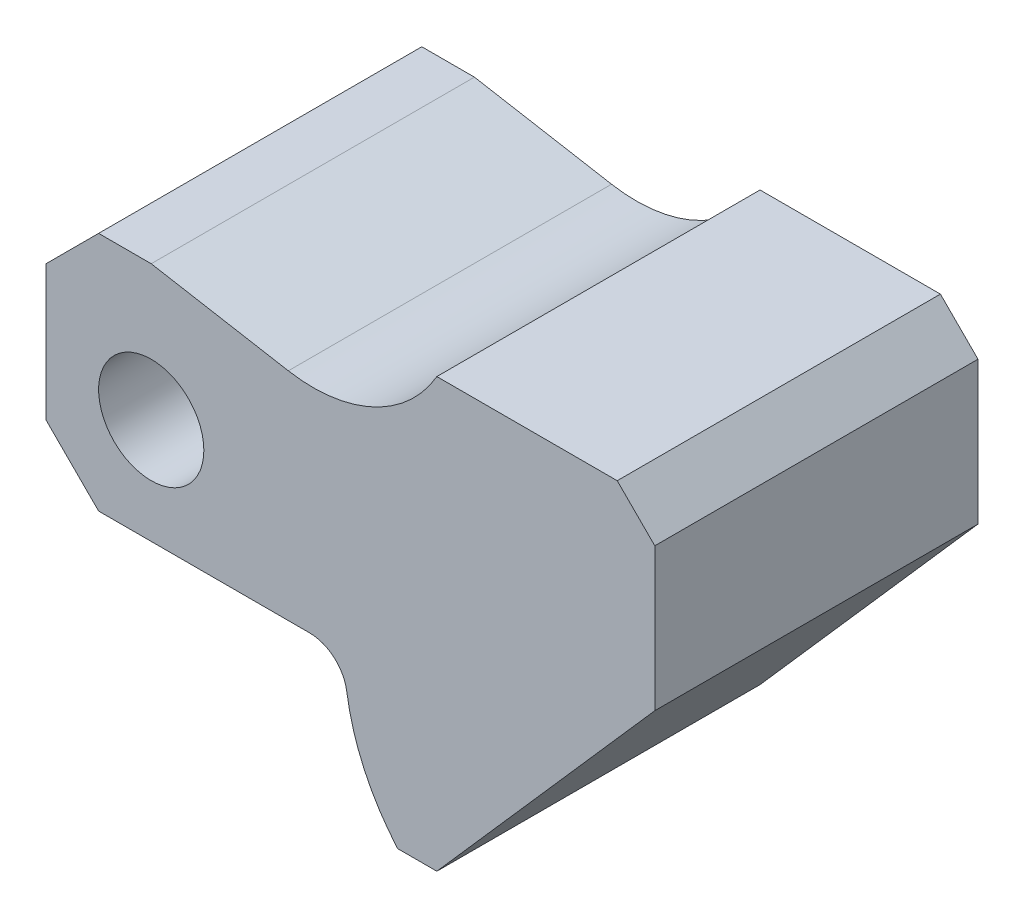
SolidWorks part; units mm, degrees
ref_plane "前基準面" through (0, 0, 0) normal (0, 0, 1) x (1, 0, 0)
ref_plane "上基準面" through (0, 0, 0) normal (0, 1, 0) x (1, 0, 0)
ref_plane "右基準面" through (0, 0, 0) normal (1, 0, 0) x (0, 0, -1)
sketch "草圖2" plane through (0, 0, 0) normal (0, 0, 1) x (1, 0, 0)
  line L0 (0, 0) -> (22.7674, 0) construction
  line L1 (0, 0) -> (0, 19.8285) construction
  line L2 (-14, 11) -> (-14, -7)
  line L3 (-14, -7) -> (-7, -14)
  line L4 (-7, -14) -> (21.0666, -14)
  line L5 (-14, 11) -> (-7, 18)
  line L6 (-7, 18) -> (0, 18)
  line L7 (0, 18) -> (18.2431, 14.7833)
  line L8 (38, 24) -> (62, 24)
  line L9 (62, 24) -> (67, 19)
  line L10 (67, 19) -> (67, 0)
  line L11 (67, 0) -> (38, -33)
  line L12 (38, -33) -> (32.7881, -33)
  circle A0 centre (0, 0) radius 7
  arc A1 (18.2431, 14.7833) -> (38, 24) centre (21.5424, 33.4946) ccw
  arc A2 (21.0666, -14) -> (26.0123, -18.2647) centre (21.0666, -19) cw
  arc A3 (26.0123, -18.2647) -> (32.7881, -33) centre (54.697, -14) ccw
  point P2 (-3.5, 18)
  point P15 (0, 0)
  point P23 (56.6381, -41.5983)
  point P27 (35.2958, -19)
  point P28 (40.9871, -33)
  dimension "D1" = 14
  dimension "D10" = 19
  dimension "D11" = 5
  dimension "D12" = 32
  dimension "D13" = 29
  dimension "D18" = 29
  dimension "D2" = 45
  dimension "D3" = 7
  dimension "D4" = 14
  dimension "D5" = 14
  dimension "D6" = 14
  dimension "D7" = 7
  dimension "D8" = 45
  dimension "D9" = 10
  dimension "D14" = 45
  dimension "D15" = 5
  dimension "D16" = 24
  dimension "D17" = 81
  dimension "D19" = 57
  dimension "D20" = 19
  dimension "D21" = 19
  dimension "D22" = 29
extrude "填料-伸長1" add sketch "草圖2" along normal blind 43
